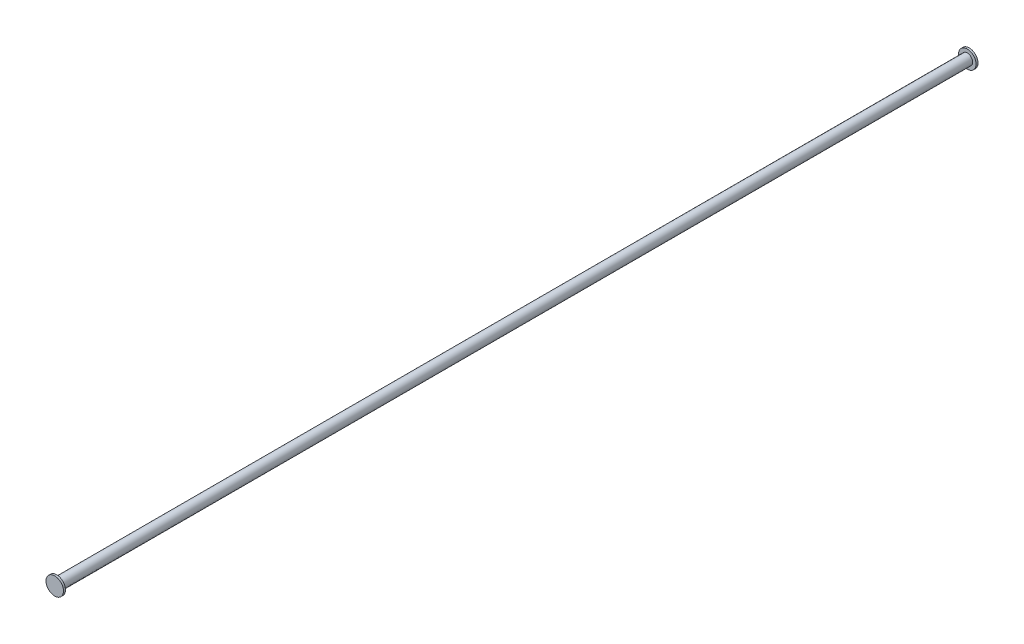
SolidWorks part; units mm, degrees
ref_plane "Front Plane" through (0, 0, 0) normal (0, 0, 1) x (1, 0, 0)
ref_plane "Top Plane" through (0, 0, 0) normal (0, 1, 0) x (1, 0, 0)
ref_plane "Right Plane" through (0, 0, 0) normal (1, 0, 0) x (0, 0, -1)
sketch "Sketch1" plane through (0, 0, 0) normal (0, 0, 1) x (1, 0, 0)
  circle A0 centre (0, 0) radius 1.375
  dimension "D1" = 2.75
extrude "Boss-Extrude1" add sketch "Sketch1" along normal mid plane 234
sketch "Sketch2" plane through (0, 0, 117) normal (0, 0, 1) x (1, 0, 0)
  circle A0 centre (0, 0) radius 2.25
  dimension "D1" = 4.5
extrude "Boss-Extrude2" add sketch "Sketch2" along normal blind 0.5
mirror "Mirror1" about plane through (0, 0, 0) normal (0, 0, 1) of "Boss-Extrude2"
